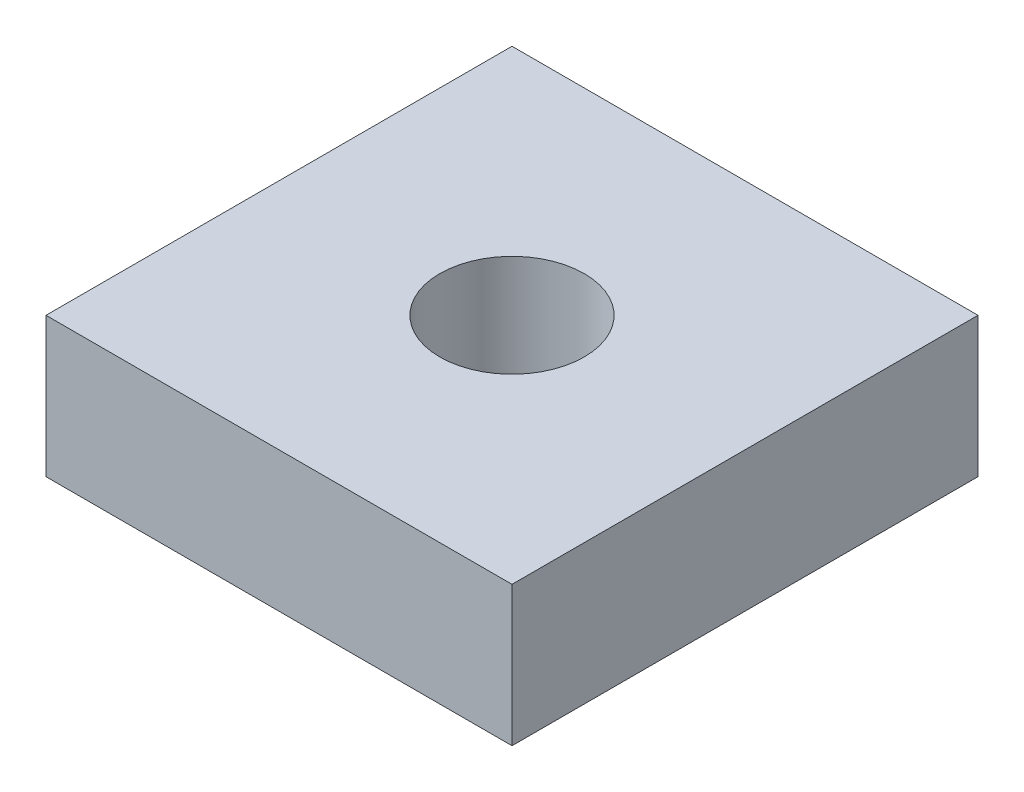
SolidWorks part; units mm, degrees
ref_plane "Alzado" through (0, 0, 0) normal (0, 0, 1) x (1, 0, 0)
ref_plane "Planta" through (0, 0, 0) normal (0, 1, 0) x (1, 0, 0)
ref_plane "Vista lateral" through (0, 0, 0) normal (1, 0, 0) x (0, 0, -1)
sketch "Croquis1" plane through (0, 0, 0) normal (0, 1, 0) x (1, 0, 0)
  line L1 (-5, -5) -> (5, -5)
  line L2 (-5, -5) -> (-5, 5)
  line L3 (-5, 5) -> (5, 5)
  line L4 (5, -5) -> (5, 5)
  line L5 (-5, -5) -> (5, 5) construction
  line L6 (-5, 5) -> (5, -5) construction
  circle A0 centre (0, 0) radius 1.55
  point P0 (0, 0)
  dimension "D1" = 3.1
  dimension "D2" = 10
  dimension "D3" = 10
extrude "Saliente-Extruir1" add sketch "Croquis1" along normal blind 3
